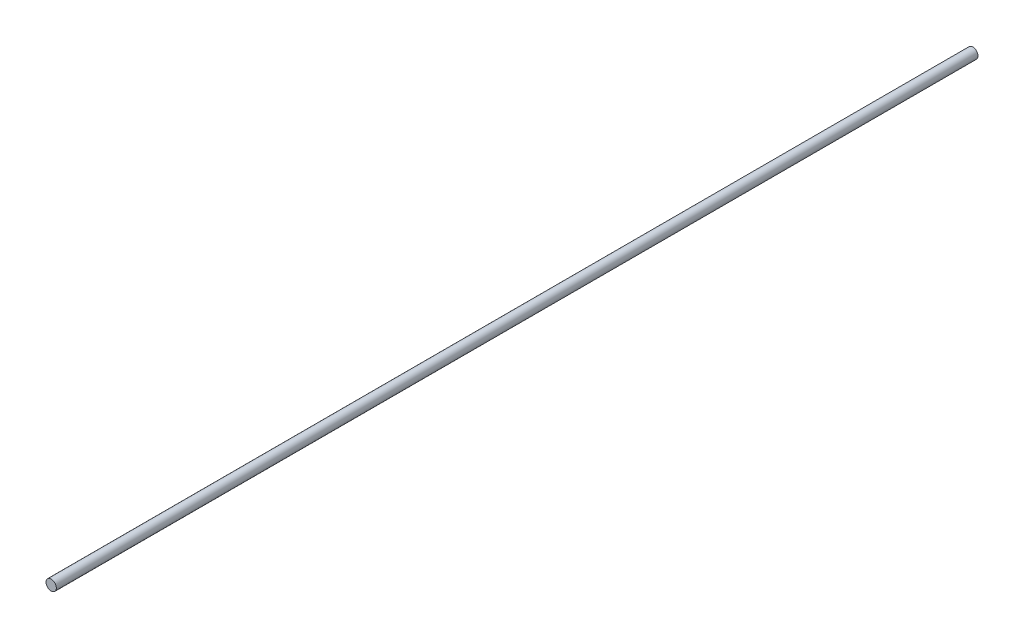
SolidWorks part; units mm, degrees
ref_plane "Front Plane" through (0, 0, 0) normal (0, 0, 1) x (1, 0, 0)
ref_plane "Top Plane" through (0, 0, 0) normal (0, 1, 0) x (1, 0, 0)
ref_plane "Right Plane" through (0, 0, 0) normal (1, 0, 0) x (0, 0, -1)
sketch "Sketch1" plane through (0, 0, 0) normal (0, 0, 1) x (1, 0, 0)
  circle A0 centre (0, 0) radius 1
  dimension "D1" = 2
extrude "Boss-Extrude1" add sketch "Sketch1" against normal blind 177.8
